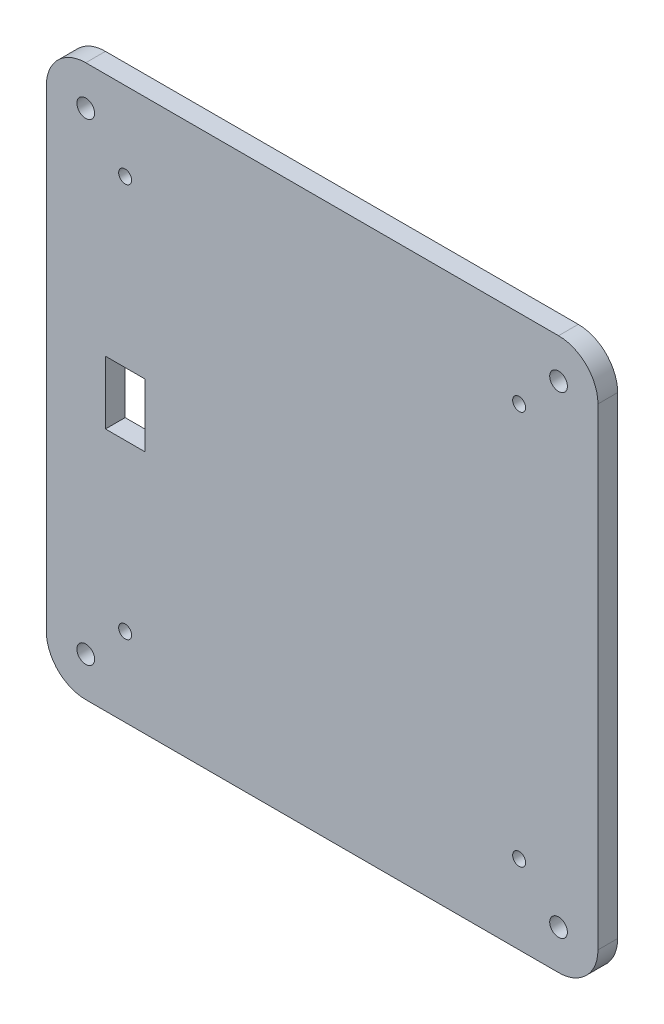
SolidWorks part; units mm, degrees
ref_plane "Спереди" through (0, 0, 0) normal (0, 0, 1) x (1, 0, 0)
ref_plane "Сверху" through (0, 0, 0) normal (0, 1, 0) x (1, 0, 0)
ref_plane "Справа" through (0, 0, 0) normal (1, 0, 0) x (0, 0, -1)
other "Configuration Table"
sketch "Eskiz_kontur" plane through (0, 0, 0) normal (0, 0, 1) x (1, 0, 0)
  line L0 (-70, -60) -> (-70, 60)
  line L1 (60, -70) -> (-60, -70)
  line L2 (-60, 70) -> (60, 70)
  line L3 (70, 60) -> (70, -60)
  line L4 (-45, -8) -> (-45, 8)
  line L5 (-45, 8) -> (-55, 8)
  line L6 (-55, 8) -> (-55, -8)
  line L7 (-55, -8) -> (-45, -8)
  arc A0 (-60, -70) -> (-70, -60) centre (-60, -60) cw
  arc A1 (-70, 60) -> (-60, 70) centre (-60, 60) cw
  arc A2 (70, -60) -> (60, -70) centre (60, -60) cw
  arc A3 (60, 70) -> (70, 60) centre (60, 60) cw
extrude "Plastina" add sketch "Eskiz_kontur" along normal blind 5
sketch "Eskiz_otverstiya" plane through (0, 0, 0) normal (0, 0, 1) x (1, 0, 0)
  circle A0 centre (-60, -60) radius 2.25
  circle A1 centre (-50, -50) radius 1.65
  circle A2 centre (60, -60) radius 2.25
  circle A3 centre (50, -50) radius 1.65
  circle A4 centre (-50, 50) radius 1.65
  circle A5 centre (-60, 60) radius 2.25
  circle A6 centre (50, 50) radius 1.65
  circle A7 centre (60, 60) radius 2.25
  dimension "d1" = 4.5
  dimension "d2" = 3.3
  dimension "d3" = 4.5
  dimension "d4" = 3.3
  dimension "d5" = 3.3
  dimension "d6" = 4.5
  dimension "d7" = 3.3
  dimension "d8" = 4.5
extrude "Otverstiya" cut sketch "Eskiz_otverstiya" against normal through all and the other way through all
equation "\"T3\" = 3"
equation "\"T5\" = 5"
equation "\"D_M3\" = 3.3"
equation "\"D_M2\" = 2.2"
equation "\"D_M3_TAP\" = 2.5"
equation "\"D_M4\" = 4.5"
equation "\"L1\" = 100"
equation "\"L2\" = 100"
equation "\"D1@Plastina\" = \"T5\""
equation "\"d1@Eskiz_otverstiya\" = \"D_M4\""
equation "\"d2@Eskiz_otverstiya\" = \"D_M3\""
equation "\"d3@Eskiz_otverstiya\" = \"D_M4\""
equation "\"d4@Eskiz_otverstiya\" = \"D_M3\""
equation "\"d5@Eskiz_otverstiya\" = \"D_M3\""
equation "\"d6@Eskiz_otverstiya\" = \"D_M4\""
equation "\"d7@Eskiz_otverstiya\" = \"D_M3\""
equation "\"d8@Eskiz_otverstiya\" = \"D_M4\""
